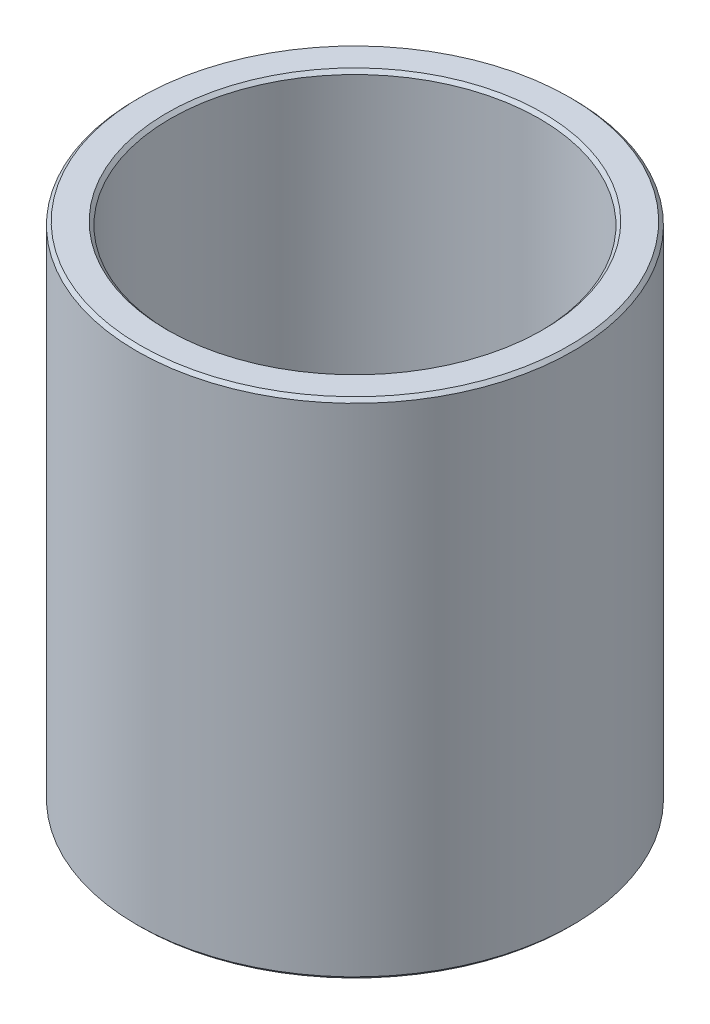
SolidWorks part; units mm, degrees
ref_plane "Front Plane" through (0, 0, 0) normal (0, 0, 1) x (1, 0, 0)
ref_plane "Top Plane" through (0, 0, 0) normal (0, 1, 0) x (1, 0, 0)
ref_plane "Right Plane" through (0, 0, 0) normal (1, 0, 0) x (0, 0, -1)
sketch "Sketch1" plane through (0, 0, 0) normal (0, 1, 0) x (1, 0, 0)
  circle A0 centre (0, 0) radius 11
  circle A1 centre (0, 0) radius 13
  dimension "D1" = 22
  dimension "D2" = 2
extrude "Boss-Extrude1" add sketch "Sketch1" along normal blind 30
chamfer "Chamfer1" distance 0.2 angle 45 4 edges at (0, 0, 11) (0, 0, 13) (0, 30, 11) (0, 30, 13)
